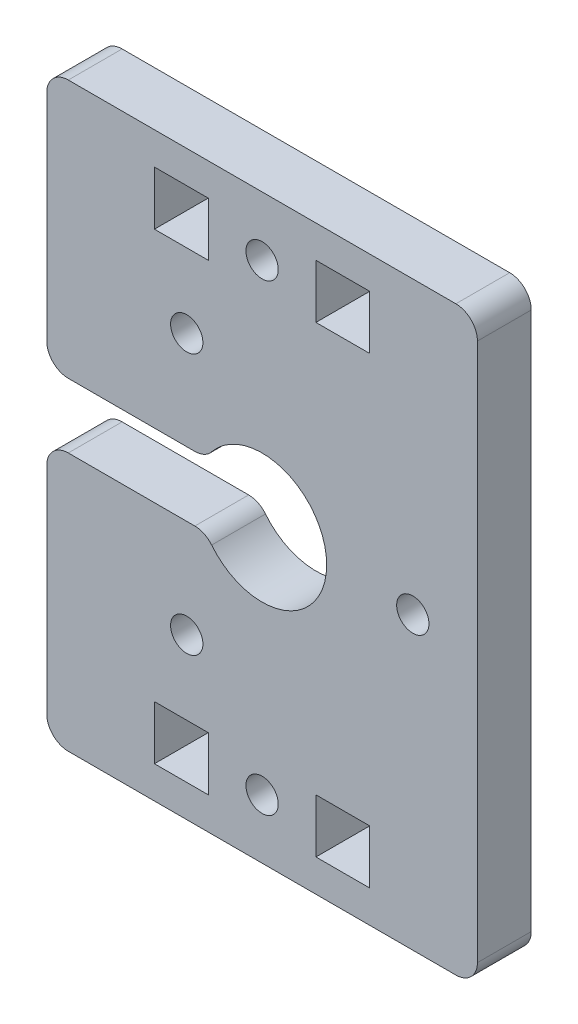
SolidWorks part; units mm, degrees
ref_plane "Plan de face" through (0, 0, 0) normal (0, 0, 1) x (1, 0, 0)
ref_plane "Plan de dessus" through (0, 0, 0) normal (0, 1, 0) x (1, 0, 0)
ref_plane "Plan de droite" through (0, 0, 0) normal (1, 0, 0) x (0, 0, -1)
sketch "Esquisse1" plane through (0, 0, 0) normal (0, 0, 1) x (1, 0, 0)
  line L0 (0, 0) -> (17.8582, 0) construction
  line L1 (-20, 27) -> (20, 27)
  line L2 (20, 27) -> (20, -27)
  line L3 (20, -27) -> (-20, -27)
  line L4 (-20, -27) -> (-20, 27) construction
  line L13 (0, 0) -> (0, 13.4404) construction
  line L14 (-20, 27) -> (-20, 3)
  line L15 (-20, 3) -> (-5.1962, 3)
  line L16 (-20, -27) -> (-20, -3)
  line L17 (-20, -3) -> (-5.1962, -3)
  circle A0 centre (0, 0) radius 6 construction
  circle A1 centre (14, 0) radius 1.5
  circle A2 centre (-7, -12.1244) radius 1.5
  circle A3 centre (-7, 12.1244) radius 1.5
  arc A4 (-5.1962, 3) -> (-5.1962, -3) centre (0, 0) cw
  point P12 (0, 0)
  line B0 (-5, 24) -> (-10, 24)
  line B1 (-5, 24) -> (-5, 19)
  line B2 (-5, 19) -> (-10, 19)
  line B3 (-10, 24) -> (-10, 19)
  line B4 (5, 24) -> (10, 24)
  line B5 (5, 24) -> (5, 19)
  line B6 (5, 19) -> (10, 19)
  line B7 (10, 24) -> (10, 19)
  line B8 (0, 21.5) -> (0, 27.7802) construction
  circle B9 centre (0, 21.5) radius 1.5
  line B10 (-5, -24) -> (-10, -24)
  line B11 (-5, -24) -> (-5, -19)
  line B12 (-5, -19) -> (-10, -19)
  line B13 (-10, -24) -> (-10, -19)
  line B14 (5, -24) -> (10, -24)
  line B15 (5, -24) -> (5, -19)
  line B16 (5, -19) -> (10, -19)
  line B17 (10, -24) -> (10, -19)
  circle B18 centre (0, -21.5) radius 1.5
sketch_block_instance "Trou M3 plots 5mm-52"
sketch_block "Trou M3 plots 5mm" parameters "D2"=3, "D1"=5, "D3"=5, "D4"=8
sketch_block_instance "Trou M3 plots 5mm-54" parameters "D2"=5.3783, "D9"=8.9498, "D1"=52.3229, "D4"=1.9713, "D5"=1.9713, "D6"=22, "D7"=23.6003, "D8"=48, "D10"=12.4801, "D11"=14.5466, "D12"=21, "D3"=3
extrude "Boss.-Extru.1" add sketch "Esquisse1" along normal blind 5
fillet "Congé1" radius 2 8 edges at (-5.1962, 3, 2.5) (20, -27, 2.5) (-20, -27, 2.5) (-20, -3, 2.5) (-5.1962, -3, 2.5) (-20, 3, 2.5) (20, 27, 2.5) (-20, 27, 2.5)
